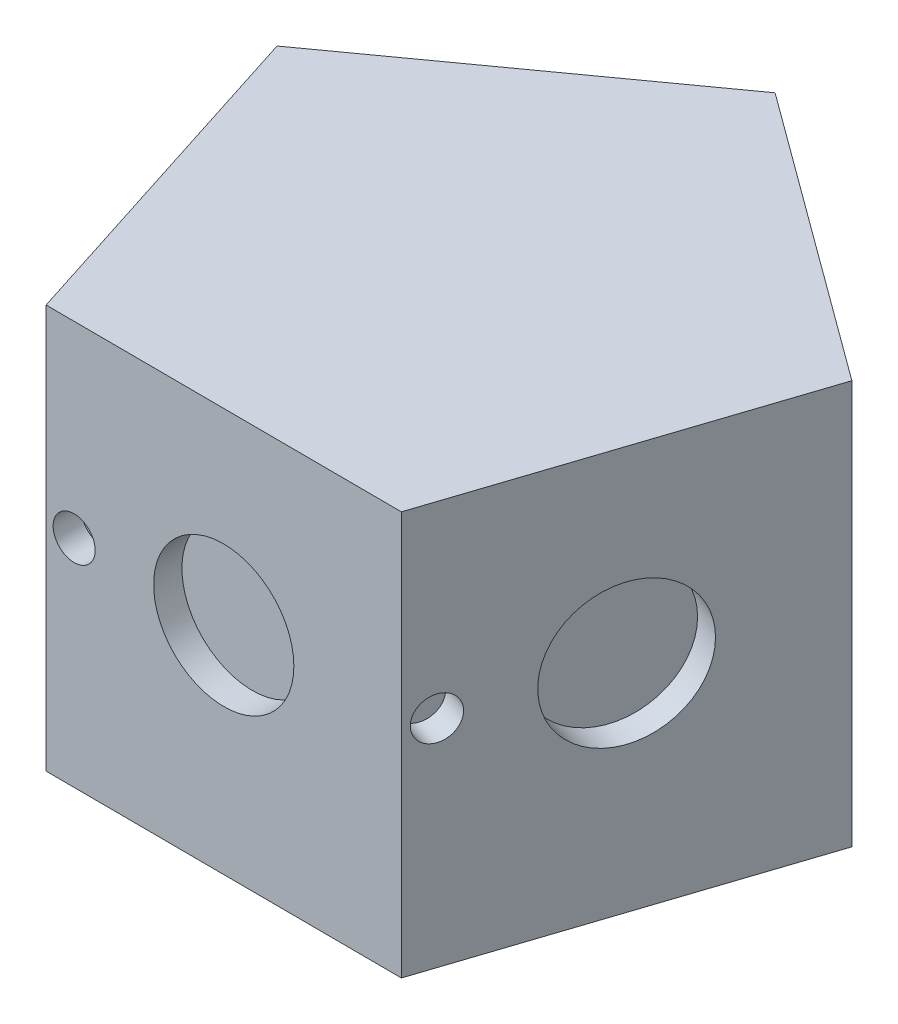
SolidWorks part; units mm, degrees
ref_plane "Front Plane" through (0, 0, 0) normal (0, 0, 1) x (1, 0, 0)
ref_plane "Top Plane" through (0, 0, 0) normal (0, 1, 0) x (1, 0, 0)
ref_plane "Right Plane" through (0, 0, 0) normal (1, 0, 0) x (0, 0, -1)
sketch "Sketch2" plane through (0, 0, 0) normal (0, 1, 0) x (1, 0, 0)
  line L1 (18.8894, -26.2313) -> (30.7846, 9.8589)
  line L2 (30.7846, 9.8589) -> (0.1365, 32.3244)
  line L3 (0.1365, 32.3244) -> (-30.7002, 10.1187)
  line L4 (-30.7002, 10.1187) -> (-19.1103, -26.0708)
  line L5 (-19.1103, -26.0708) -> (18.8894, -26.2313)
  circle A0 centre (0, 0) radius 26.1513 construction
  dimension "D1" = 38
extrude "Boss-Extrude1" add sketch "Sketch2" along normal blind 40
sketch "Sketch3" plane through (-0.1105, 0, 26.151) normal (-0.0042, 0, 1) x (1, 0, 0.0042)
  line L0 (-19, 40) -> (19, 0) construction
  line L1 (19, 0) -> (19, 40) construction
  line L2 (19, 40) -> (-19, 0) construction
  line L3 (0, 20) -> (-16, 20) construction
  circle A0 centre (0, 20) radius 7.5
  circle A1 centre (-16, 20) radius 2.25
  point P4 (0, 20)
  dimension "D1" = 15
  dimension "D3" = 4.5
  dimension "D2" = 16
extrude "Cut-Extrude1" cut sketch "Sketch3" against normal blind 3
sketch "Sketch4" plane through (24.837, 0, 8.1862) normal (0.9497, 0, 0.313) x (0.313, 0, -0.9497)
  line L0 (-19, 40) -> (19, 0) construction
  line L1 (19, 0) -> (19, 40) construction
  line L2 (19, 40) -> (-19, 0) construction
  line L3 (0, 20) -> (-16, 20) construction
  circle A0 centre (0, 20) radius 7.5
  circle A1 centre (-16, 20) radius 2.25
  point P4 (0, 20)
  dimension "D1" = 15
  dimension "D3" = 4.5
  dimension "D2" = 16
extrude "Cut-Extrude2" cut sketch "Sketch4" against normal blind 3
sketch "Sketch5" plane through (15.4605, 0, -21.0917) normal (0.5912, 0, -0.8065) x (-0.8065, 0, -0.5912)
  line L0 (-19, 40) -> (19, 0) construction
  line L1 (19, 0) -> (19, 40) construction
  line L2 (19, 40) -> (-19, 0) construction
  line L3 (0, 20) -> (-16, 20) construction
  circle A0 centre (0, 20) radius 7.5
  circle A1 centre (-16, 20) radius 2.25
  point P4 (0, 20)
  dimension "D1" = 15
  dimension "D3" = 4.5
  dimension "D2" = 16
extrude "Cut-Extrude3" cut sketch "Sketch5" against normal blind 3
sketch "Sketch6" plane through (-15.2818, 0, -21.2215) normal (-0.5844, 0, -0.8115) x (-0.8115, 0, 0.5844)
  line L0 (-19, 40) -> (19, 0) construction
  line L1 (19, 0) -> (19, 40) construction
  line L2 (19, 40) -> (-19, 0) construction
  line L3 (0, 20) -> (-16, 20) construction
  circle A0 centre (0, 20) radius 7.5
  circle A1 centre (-16, 20) radius 2.25
  point P4 (0, 20)
  dimension "D1" = 15
  dimension "D3" = 4.5
  dimension "D2" = 16
extrude "Cut-Extrude4" cut sketch "Sketch6" against normal blind 3
sketch "Sketch7" plane through (-24.9052, 0, 7.9761) normal (-0.9524, 0, 0.305) x (0.305, 0, 0.9524)
  line L0 (-19, 40) -> (19, 0) construction
  line L1 (19, 0) -> (19, 40) construction
  line L2 (19, 40) -> (-19, 0) construction
  line L3 (0, 20) -> (-16, 20) construction
  circle A0 centre (0, 20) radius 7.5
  circle A1 centre (-16, 20) radius 2.25
  point P4 (0, 20)
  dimension "D1" = 15
  dimension "D3" = 4.5
  dimension "D2" = 16
extrude "Cut-Extrude5" cut sketch "Sketch7" against normal blind 3
sketch "Sketch8" plane through (0, 0, 0) normal (0, -1, 0) x (1, 0, 0)
  line L1 (30.7846, -9.8589) -> (18.8894, 26.2313)
  line L2 (18.8894, 26.2313) -> (-19.1103, 26.0708)
  line L3 (-19.1103, 26.0708) -> (-30.7002, -10.1187)
  line L4 (-30.7002, -10.1187) -> (0.1365, -32.3244)
  line L5 (0.1365, -32.3244) -> (30.7846, -9.8589)
  circle A0 centre (0, 0) radius 26.1513 construction
extrude "Boss-Extrude2" add sketch "Sketch8" along normal blind 3
